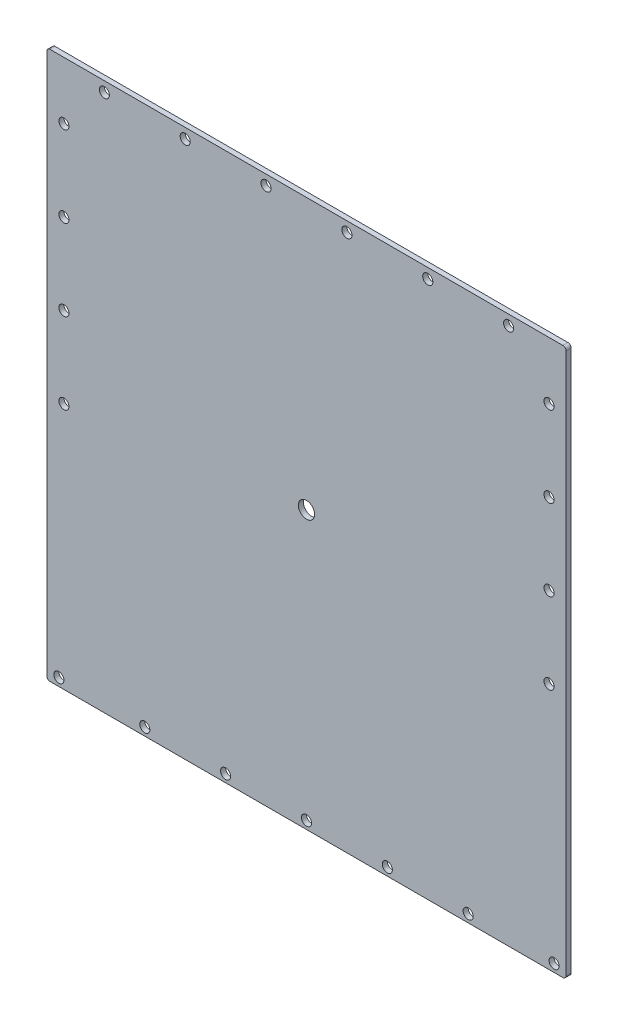
SolidWorks part; units mm, degrees
material "6061 Alloy"
ref_plane "Front Plane" through (0, 0, 0) normal (0, 0, 1) x (1, 0, 0)
ref_plane "Top Plane" through (0, 0, 0) normal (0, 1, 0) x (1, 0, 0)
ref_plane "Right Plane" through (0, 0, 0) normal (1, 0, 0) x (0, 0, -1)
sketch "Sketch2" plane through (0, 0, 0) normal (0, 0, 1) x (1, 0, 0)
  line L0 (0, -176.7623) -> (165.1, -176.7623)
  line L1 (0, 0) -> (165.1, 0)
  line L5 (82.55, 0) -> (82.55, -176.7623) construction
  line L6 (165.1, 0) -> (165.1, -176.7623)
  line L7 (0, 0) -> (0, -176.7623)
  line L8 (0, 0) -> (0, -176.7623)
  line L9 (0, -171.98) -> (165.1, -171.98)
  line L10 (1, 0) -> (1, -171.98)
  line L11 (164.1, -171.98) -> (164.1, 0)
  circle A31 centre (31.75, -169.48) radius 1.5875
  circle A32 centre (57.15, -169.48) radius 1.5875
  circle A33 centre (82.55, -169.48) radius 1.5875
  circle A34 centre (107.95, -169.48) radius 1.5875
  circle A35 centre (133.35, -169.48) radius 1.5875
  circle A63 centre (6.35, -18.05) radius 1.5875
  circle A65 centre (160.3375, -169.48) radius 1.5875
  circle A66 centre (4.7625, -169.48) radius 1.5875
  circle A67 centre (82.55, -85) radius 2.5527
  circle A69 centre (19.05, -3.175) radius 1.5875
  circle A70 centre (44.45, -3.175) radius 1.5875
  circle A71 centre (69.85, -3.175) radius 1.5875
  circle A72 centre (95.25, -3.175) radius 1.5875
  circle A73 centre (120.65, -3.175) radius 1.5875
  circle A74 centre (146.05, -3.175) radius 1.5875
  circle A76 centre (6.35, -43.45) radius 1.5875
  circle A77 centre (6.35, -68.85) radius 1.5875
  circle A78 centre (6.35, -94.25) radius 1.5875
  circle A81 centre (158.75, -68.85) radius 1.5875
  circle A82 centre (158.75, -94.25) radius 1.5875
  circle A83 centre (158.75, -43.45) radius 1.5875
  circle A84 centre (158.75, -18.05) radius 1.5875
  dimension "D9" = 3.175
  dimension "D4" = 3.175
  dimension "D21" = 5.1054
  dimension "D1" = 165.1
  dimension "D23" = 25.4
  dimension "D5" = 176.7623
  dimension "D8" = 31.75
  dimension "D11" = 7.2823
  dimension "D10" = 19.05
  dimension "D12" = 3.175
  dimension "D14" = 25.4
  dimension "D3" = 18.05
  dimension "D6" = 6.35
  dimension "D15" = 25.4
  dimension "D16" = 2.5
  dimension "D17" = 4.7625
  dimension "D18" = 1
  dimension "D19" = 1
  dimension "D20" = 85
  dimension "D22" = 5
  dimension "D13" = 3
  dimension "D7" = 4
extrude "Boss-Extrude2" add sketch "Sketch2" along normal blind 1.5875
fillet "Fillet1" radius 1 4 edges at (1, -171.98, 0.7937) (1, 0, 0.7937) (164.1, 0, 0.7937) (164.1, -171.98, 0.7937)
equation "\"D19@Sketch2\"=\"D18@Sketch2\""
equation "\"D9@Sketch2\"=\"D4@Sketch2\""
